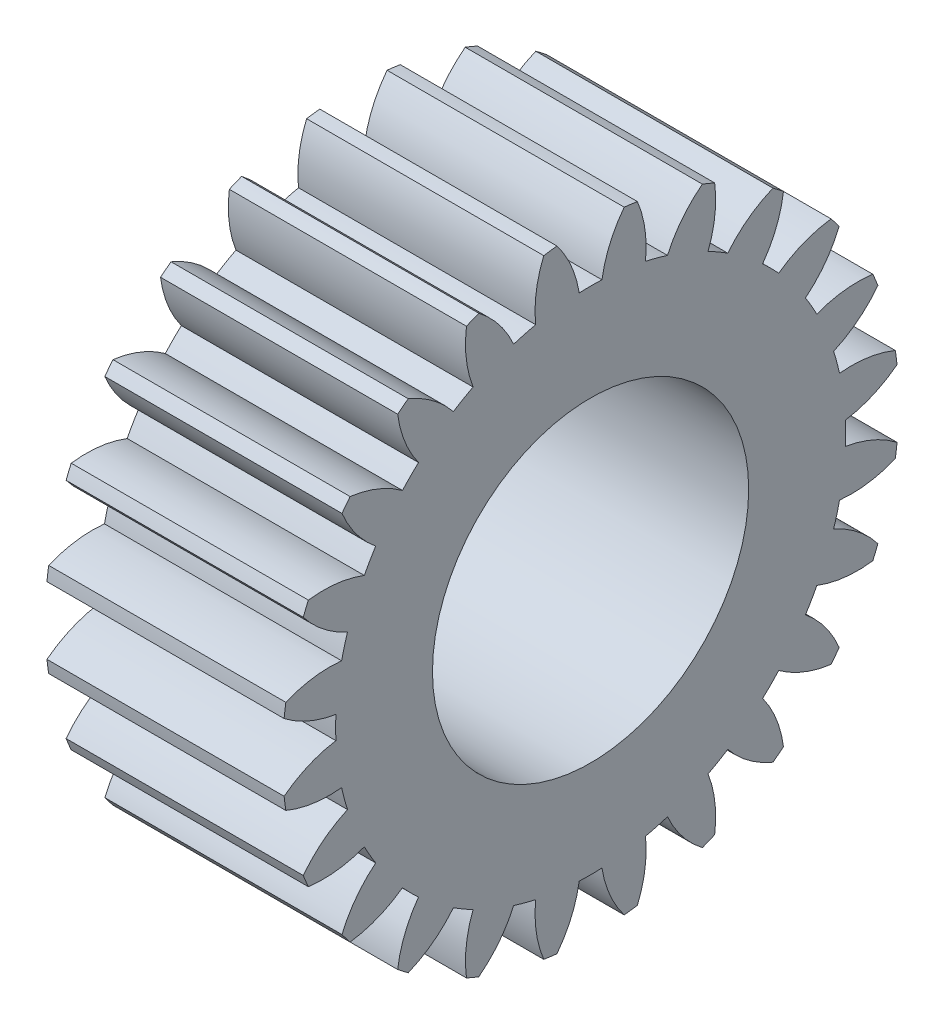
SolidWorks part; units mm, degrees
ref_plane "Plane1" through (0, 0, 0) normal (0, 0, 1) x (1, 0, 0)
ref_plane "Plane2" through (0, 0, 0) normal (0, 1, 0) x (1, 0, 0)
ref_plane "Plane3" through (0, 0, 0) normal (1, 0, 0) x (0, 0, -1)
sketch "HoldingSke" plane through (0, 0, 0) normal (0, 1, 0) x (1, 0, 0)
  line L0 (0, 0) -> (0.3045, -0.1356)
  line L1 (-15, 0) -> (100, 0) construction
  line L2 (0, 0) -> (-2.1039, 2.3779)
  line L3 (0, 0) -> (-11.863, 4.5341)
  line L4 (0, 0) -> (7.8894, 3.5126)
  line L5 (0, 0) -> (-46.8476, -17.4728)
  line L6 (0, 0) -> (-24.8689, -16.7791)
  line L7 (-2.1039, 2.3779) -> (8.6586, 51.2059)
  line L8 (-76.2, 54.61) -> (-72.9, 54.61)
  line L9 (-71.009, 38.7566) -> (-53.1078, 45.2721)
  line L10 (-76.2, 71.12) -> (104.1128, 71.12)
  line L11 (0, 0) -> (-30, 0)
  line L12 (-76.2, 101.6) -> (-76.093, 101.6)
  line L13 (24.9733, 27.94) -> (52.9518, 28.4284)
  line L14 (24.9733, 27.94) -> (24.9743, 27.94)
  line L15 (24.9733, 27.94) -> (100.4006, 29.5858)
  line L16 (-63.627, -3) -> (-12.827, -3)
  circle A0 centre (0, 0) radius 20
  circle A1 centre (0, 0) radius 32.249
  circle A2 centre (0, 0) radius 37.5
  circle A3 centre (0, 0) radius 20
  dimension "MHD" = 64.498
  dimension "Hub_dia" = 75
  dimension "Bore" = 40
  dimension "MBD" = 40
  dimension "Num_teeth" = 24
  dimension "Pitch" = 0.3333
  dimension "Overall_len" = 50
  dimension "Show_teeth" = 24
  dimension "Thickness" = 30
  dimension "OAL" = 50.0001
  dimension "T_dim" = 3.3
  dimension "Ap" = 20
  dimension "H" = 19.05
  dimension "Pitch_radius" = 180.3128
  dimension "Width" = 30
  dimension "Backlash" = 0.107
  dimension "Addendum_fac" = 1
  dimension "Dedendum_fac" = 1.25
  dimension "Clearance_fac" = 0.25
  dimension "Dedendum_add" = 0.001
  dimension "Module" = 3
sketch "BasProSke" plane through (0, 0, 0) normal (0, 1, 0) x (1, 0, 0)
  line L0 (-10, 0) -> (60, 0) construction
  line L1 (0, 0) -> (0, 39)
  line L2 (0, 0) -> (30, 0)
  line L3 (30, 0) -> (30, 39)
  line L4 (30, 39) -> (0, 39)
  dimension "Thickness" = 30
  dimension "Diameter" = 78
revolve "Base-Revolve" add sketch "BasProSke" angle 360 about L0
sketch "TooCutSke" plane through (0, 0, 0) normal (1, 0, 0) x (0, 0, -1)
  line L1 (0, 0) -> (0, 107) construction
  line L2 (0, 0) -> (-2.5417, 35.9102) construction
  line L3 (0, 0) -> (-9.3808, 71.2546) construction
  line L4 (-2.5417, 35.9102) -> (-4.6904, 35.6273) construction
  arc A0 (1.4397, 32.2168) -> (-1.4397, 32.2168) centre (0, 0) ccw
  arc A1 (4.273, 38.7908) -> (-4.273, 38.7908) centre (0, 0) ccw
  circle A2 centre (0, 0) radius 36 construction
  circle A3 centre (0, 0) radius 33.8289 construction
  arc A4 (-1.4397, 32.2168) -> (-4.273, 38.7908) centre (-15.6654, 29.9832) ccw
  arc A5 (4.273, 38.7908) -> (1.4397, 32.2168) centre (15.6654, 29.9832) ccw
  dimension "Root_dia" = 64.498
  dimension "Overcut_dia" = 78.0508
  dimension "Pitch_dia" = 72
  dimension "Base_dia" = 67.6579
  dimension "Flank_rad" = 14.4
  dimension "Half_ang" = 7.5
  dimension "Half_CT" = 2.1673
extrude "ToothCut" cut sketch "TooCutSke" along normal through all
fillet "Breaks" [suppressed] radius 0.06
fillet "RootFillets" [suppressed] radius 0.751
pattern_circular "TeethCuts" count 24 every 15 about axis through (-10, 0, 0) along (1, 0, 0) of "ToothCut", "RootFillets", "Breaks"
sketch "HubNeaOneSke" plane through (0, 0, 0) normal (-1, 0, 0) x (0, 0, 1)
  circle A0 centre (0, 0) radius 32.249
  dimension "Diameter" = 64.498
extrude "HubNearOne" [suppressed] add sketch "HubNeaOneSke" along normal blind 20.0001
sketch "HubNeaBotSke" plane through (0, 0, 0) normal (-1, 0, 0) x (0, 0, 1)
  circle A0 centre (0, 0) radius 32.249
  dimension "Diameter" = 64.498
extrude "HubNearBoth" [suppressed] add sketch "HubNeaBotSke" along normal blind 10
ref_plane "FarPln" through (30, 0, 0) normal (1, 0, 0) x (0, 0, -1)
sketch "HubFarSke" plane through (30, 0, 0) normal (1, 0, 0) x (0, 0, -1)
  circle A0 centre (0, 0) radius 32.249
  dimension "Diameter" = 64.498
extrude "HubFar" [suppressed] add sketch "HubFarSke" along normal blind 10
sketch "BorSke" plane through (0, 0, 0) normal (1, 0, 0) x (0, 0, -1)
  circle A0 centre (0, 0) radius 20
  dimension "Diameter" = 40
extrude "Bore" cut sketch "BorSke" along normal mid plane 100.0001
sketch "KeySke" plane through (0, 0, 0) normal (1, 0, 0) x (0, 0, -1)
  line L0 (-6, 0) -> (-6, 23.3)
  line L1 (-6, 23.3) -> (6, 23.3)
  line L2 (6, 23.3) -> (6, 0)
  line L3 (0, 0) -> (0, 34) construction
  line L4 (-6, 0) -> (6, 0)
  dimension "Offset" = 23.3
  dimension "Width" = 12
extrude "Keyway" [suppressed] cut sketch "KeySke" along normal mid plane 100.0001
pattern_circular "Keyway2" [suppressed] count 2 every 90 about axis through (-10, 0, 0) along (1, 0, 0)
equation "' \"Module@HoldingSke\" = 6.35"
equation "' \"Num_teeth@HoldingSke\" = 12"
equation "' \"Ap@HoldingSke\" =  20"
equation "' \"Ap@HoldingSke\" = 20"
equation "' \"Width@HoldingSke\" = 0.5 * 25.4"
equation "' \"Hub_dia@HoldingSke\"= 1 * 25.4"
equation "' \"Hub_dia@HoldingSke\" = 1 * 25.4"
equation "' \"Overall_len@HoldingSke\" = 1.0 * 25.4"
equation "' \"Bore@HoldingSke\" = 0.75 * 25.4"
equation "' \"T_dim@HoldingSke\" = 0.1 * 25.4"
equation "' \"Width@KeySke\" = 0.25 * 25.4"
equation "' \"Show_teeth@HoldingSke\" = 13"
equation "' \"Backlash@HoldingSke\" = 0.009 * 25.4"
equation "' \"Addendum_fac@HoldingSke\" = 1.0"
equation "' \"Dedendum_fac@HoldingSke\" = 1.25"
equation "' \"Dedendum_add@HoldingSke\" = 0.00005 * 25.4"
equation "' \"Clearance_fac@HoldingSke\" = 0.25"
equation "\"Pitch@HoldingSke\" = 1 / \"Module@HoldingSke\""
equation "\"Overcut_dia@TooCutSke\" = (\"Num_teeth@HoldingSke\" + 2 * \"Addendum_fac@HoldingSke\") / \"Pitch@HoldingSke\" + 0.002 * 25.4"
equation "\"Pitch_dia@TooCutSke\" = \"Num_teeth@HoldingSke\" / \"Pitch@HoldingSke\""
equation "\"Base_dia@TooCutSke\" = \"Num_teeth@HoldingSke\" / \"Pitch@HoldingSke\" * cos((\"Ap@HoldingSke\"  * 3.14159265 / 180))"
equation "\"Root_dia@TooCutSke\" = (\"Num_teeth@HoldingSke\" + 2) / \"Pitch@HoldingSke\" - 2 * (\"Addendum_fac@HoldingSke\" + \"Dedendum_fac@HoldingSke\") / \"Pitch@HoldingSke\" - \"Dedendum_add@HoldingSke\" * 2"
equation "\"Half_ang@TooCutSke\" = 180 / \"Num_teeth@HoldingSke\""
equation "\"Half_CT@TooCutSke\" = \"Num_teeth@HoldingSke\" / \"Pitch@HoldingSke\" * sin((3.14159265 / 2 / \"Num_teeth@HoldingSke\")) / 2 - 7 * \"Backlash@HoldingSke\" / 4"
equation "\"Flank_rad@TooCutSke\" = \"Num_teeth@HoldingSke\" / \"Pitch@HoldingSke\" / 5"
equation "\"Radius@RootFillets\" = \"Clearance_fac@HoldingSke\" / \"Pitch@HoldingSke\" + \"Dedendum_add@HoldingSke\""
equation "\"Break_rad@Breaks\" = 0.02 / \"Pitch@HoldingSke\""
equation "\"Thickness@HoldingSke\" = \"Width@HoldingSke\""
equation "\"OAL@HoldingSke\" = \"Thickness@HoldingSke\""
equation "\"MHD@HoldingSke\" = (\"Num_teeth@HoldingSke\" + 2) / \"Pitch@HoldingSke\" - 2 * (\"Addendum_fac@HoldingSke\" + \"Dedendum_fac@HoldingSke\")  / \"Pitch@HoldingSke\" - \"Dedendum_add@HoldingSke\" * 2"
equation "\"MBD@HoldingSke\" = (\"Num_teeth@HoldingSke\" + 2) / \"Pitch@HoldingSke\" - 2 * (\"Addendum_fac@HoldingSke\" + \"Dedendum_fac@HoldingSke\")  / \"Pitch@HoldingSke\" - \"Dedendum_add@HoldingSke\" * 2 - 0.002 * 25.4"
equation "\"MHD@HoldingSke\" = ((sgn( \"MHD@HoldingSke\" - \"Hub_dia@HoldingSke\" )-1)*( \"MHD@HoldingSke\" - \"Hub_dia@HoldingSke\" ))/-2+ \"Hub_dia@HoldingSke\""
equation "\"MBD@HoldingSke\" = ((sgn( \"MBD@HoldingSke\" - \"Bore@HoldingSke\" )-1)*( \"MBD@HoldingSke\" - \"Bore@HoldingSke\" ))/-2+ \"Bore@HoldingSke\""
equation "\"OAL@HoldingSke\" = ((sgn( \"OAL@HoldingSke\" - \"Overall_len@HoldingSke\" )+1)*( \"OAL@HoldingSke\" - \"Overall_len@HoldingSke\" ))/2 + \"Overall_len@HoldingSke\" + 0.000002 * 25.4"
equation "\"Num_teeth@TeethCuts\" = int( \"Show_teeth@HoldingSke\" ) + 1"
equation "\"Num_teeth@TeethCuts\" = ((sgn( \"Num_teeth@TeethCuts\" - \"Num_teeth@HoldingSke\" )-1)*( \"Num_teeth@TeethCuts\" - \"Num_teeth@HoldingSke\" ))/-2+ \"Num_teeth@HoldingSke\""
equation "\"Num_teeth@TeethCuts\" = ((sgn( \"Num_teeth@TeethCuts\" - 2.0)+1)*( \"Num_teeth@TeethCuts\" - 2.0))/2 +2.0"
equation "\"Angle@TeethCuts\" = 360.0 / \"Num_teeth@HoldingSke\""
equation "\"Diameter@BasProSke\" = (\"Num_teeth@HoldingSke\" + 2 * \"Addendum_fac@HoldingSke\") / \"Pitch@HoldingSke\""
equation "\"Thickness@BasProSke\"  = \"Thickness@HoldingSke\""
equation "' \"Fillet_rad@BasProSke\" =  \"Thickness@HoldingSke\" * 0.05"
equation "' \"Fillet_rad@BasProSke\" = \"Thickness@HoldingSke\" * 0.05"
equation "\"MHD@HoldingSke\" = ((sgn( \"MHD@HoldingSke\" - \"Root_dia@TooCutSke\" )-1)*( \"MHD@HoldingSke\" - \"Root_dia@TooCutSke\" ))/-2+ \"Root_dia@TooCutSke\""
equation "\"Diameter@HubNeaOneSke\" = \"MHD@HoldingSke\""
equation "\"Length@HubNearOne\" = \"OAL@HoldingSke\" - \"Thickness@BasProSke\""
equation "\"Diameter@HubNeaBotSke\" = \"MHD@HoldingSke\""
equation "\"Length@HubNearBoth\" = ( \"OAL@HoldingSke\" - \"Thickness@BasProSke\" ) / 2.0"
equation "\"Thickness@FarPln\" = \"Thickness@BasProSke\""
equation "\"Diameter@HubFarSke\" = \"MHD@HoldingSke\""
equation "\"Length@HubFar\" = ( \"OAL@HoldingSke\" - \"Thickness@BasProSke\" ) / 2.0"
equation "\"Diameter@BorSke\" = \"MBD@HoldingSke\""
equation "\"D1@Bore\" = \"OAL@HoldingSke\" * 2.0"
equation "\"D1@Keyway\" = \"OAL@HoldingSke\" * 2.0"
equation "\"Offset@KeySke\" = \"T_dim@HoldingSke\" + \"MBD@HoldingSke\" / 2.0"
